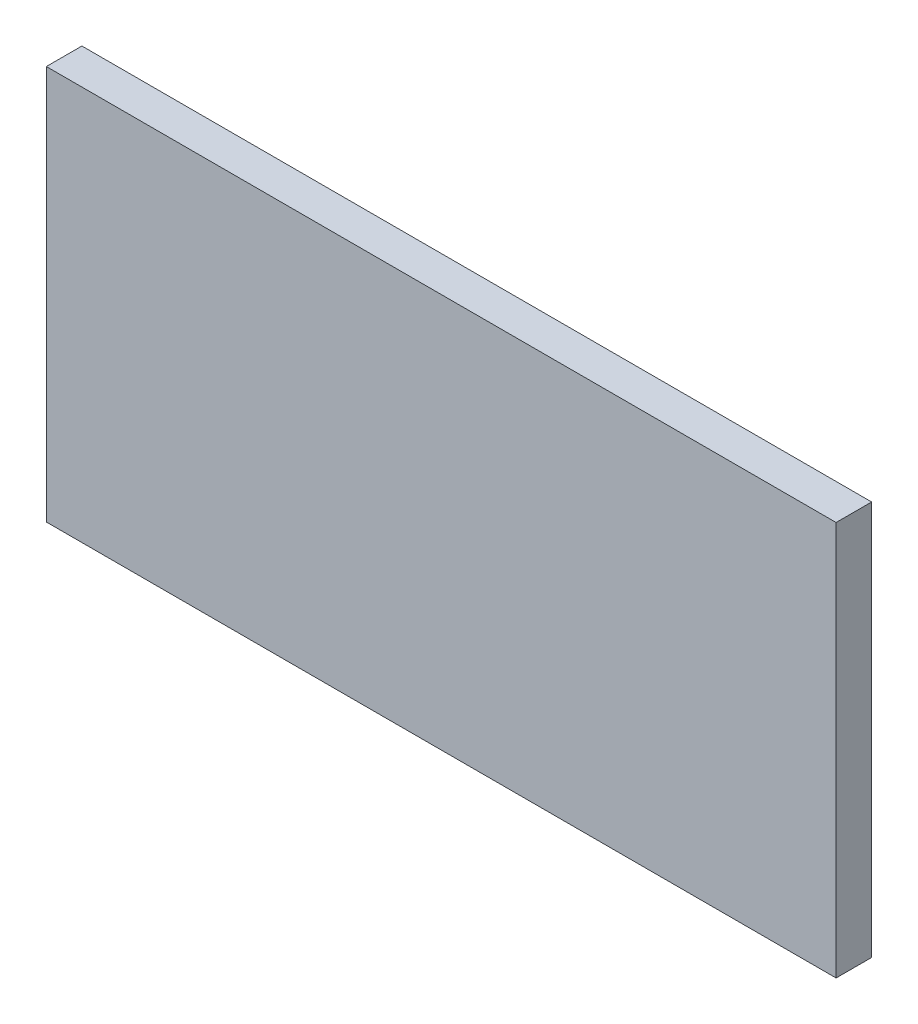
SolidWorks part; units mm, degrees
ref_plane "Alzado" through (0, 0, 0) normal (0, 0, 1) x (1, 0, 0)
ref_plane "Planta" through (0, 0, 0) normal (0, 1, 0) x (1, 0, 0)
ref_plane "Vista lateral" through (0, 0, 0) normal (1, 0, 0) x (0, 0, -1)
ref_plane "Plano2" through (0, 0, 22.9) normal (0, 0, 1) x (1, 0, 0)
sketch "Croquis4" plane through (0, 0, 22.9) normal (0, 0, 1) x (1, 0, 0)
  line L1 (4.1666, -10.448) -> (-18.0554, -10.448)
  line L2 (4.1666, -10.448) -> (4.1666, 0.652)
  line L3 (4.1666, 0.652) -> (-18.0554, 0.652)
  line L4 (-18.0554, -10.448) -> (-18.0554, 0.652)
extrude "Saliente-Extruir1" add sketch "Croquis4" against normal up to vertex (1 mm away) contours L1 L4 L3 L2
